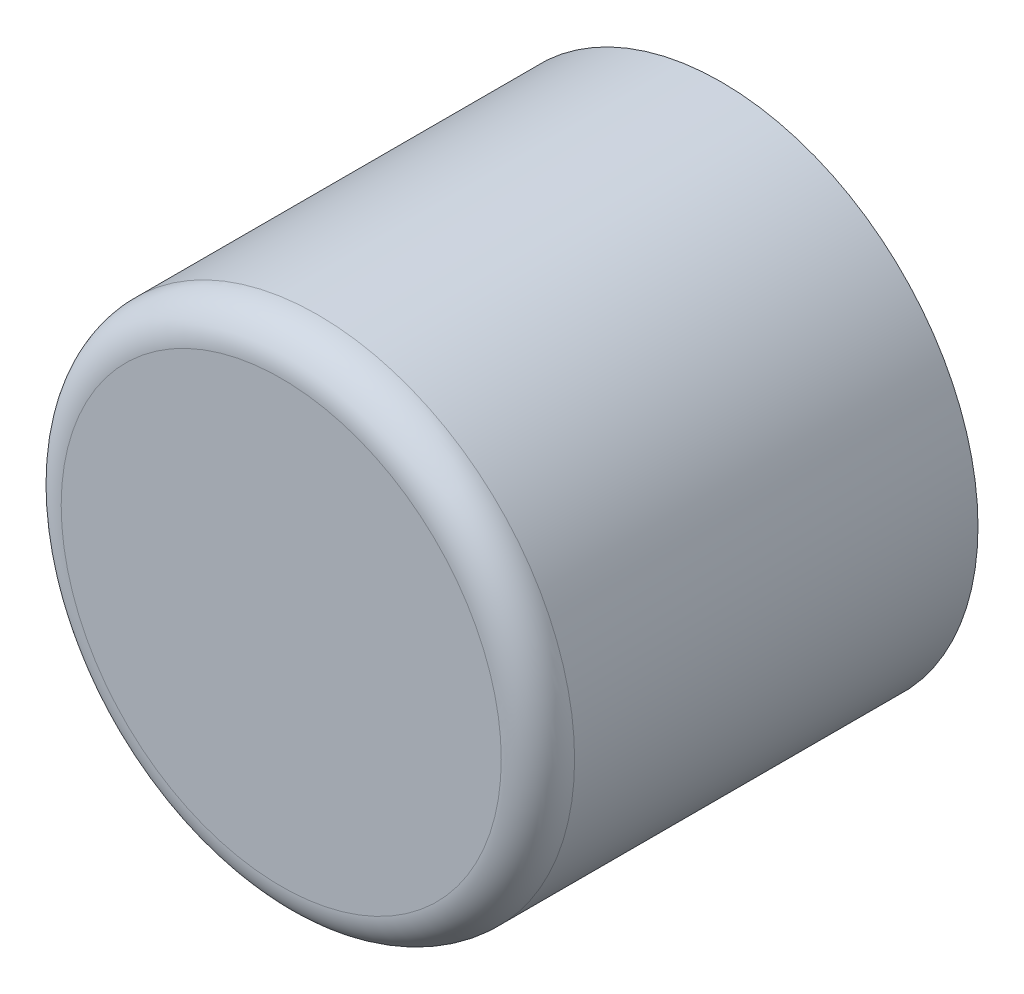
SolidWorks part; units mm, degrees
ref_plane "Alzado" through (0, 0, 0) normal (0, 0, 1) x (1, 0, 0)
ref_plane "Planta" through (0, 0, 0) normal (0, 1, 0) x (1, 0, 0)
ref_plane "Vista lateral" through (0, 0, 0) normal (1, 0, 0) x (0, 0, -1)
sketch "Croquis1" plane through (0, 0, 0) normal (0, 0, 1) x (1, 0, 0)
  circle A0 centre (0, 0) radius 105
  circle A1 centre (0, 0) radius 95
  dimension "D1" = 210
  dimension "D2" = 190
extrude "Saliente-Extruir1" add sketch "Croquis1" along normal blind 180
sketch "Croquis2" plane through (0, 0, 180) normal (0, 0, 1) x (1, 0, 0)
  circle A0 centre (0, 0) radius 101.5
extrude "Saliente-Extruir2" add sketch "Croquis2" against normal blind 20
fillet "Redondeo1" radius 15 1 edges at (105, 0, 180)
